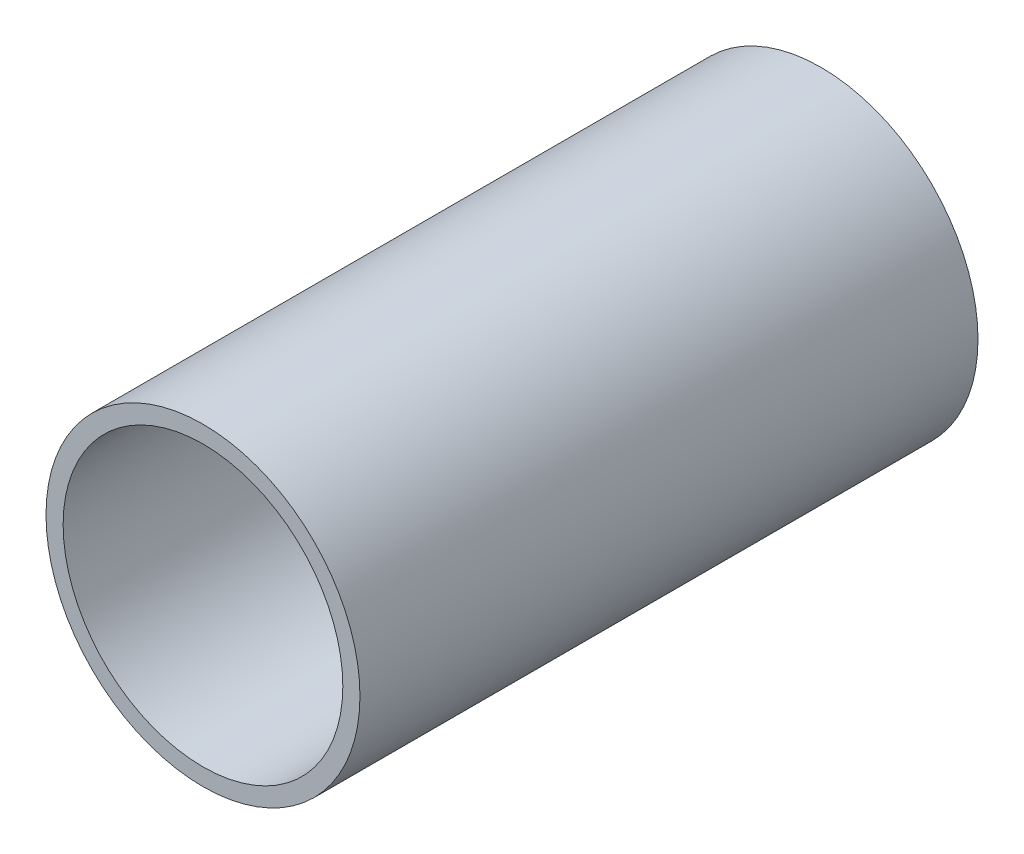
SolidWorks part; units mm, degrees
ref_plane "Plano frontal" through (0, 0, 0) normal (0, 0, 1) x (1, 0, 0)
ref_plane "Plano superior" through (0, 0, 0) normal (0, 1, 0) x (1, 0, 0)
ref_plane "Plano direito" through (0, 0, 0) normal (1, 0, 0) x (0, 0, -1)
sketch "Esboço2" plane through (0, 0, 0) normal (1, 0, 0) x (0, 0, -1)
  line L0 (0, 33.94) -> (150, 33.94)
  line L1 (150, 33.94) -> (150, 38.1)
  line L2 (150, 38.1) -> (0, 38.1)
  line L3 (0, 38.1) -> (0, 33.94)
  line L4 (0, 0) -> (44.7277, 0) construction
  dimension "D1" = 76.2
  dimension "D2" = 4.16
  dimension "D3" = 150
revolve "Revolução1" add sketch "Esboço2" angle 360 about L4
